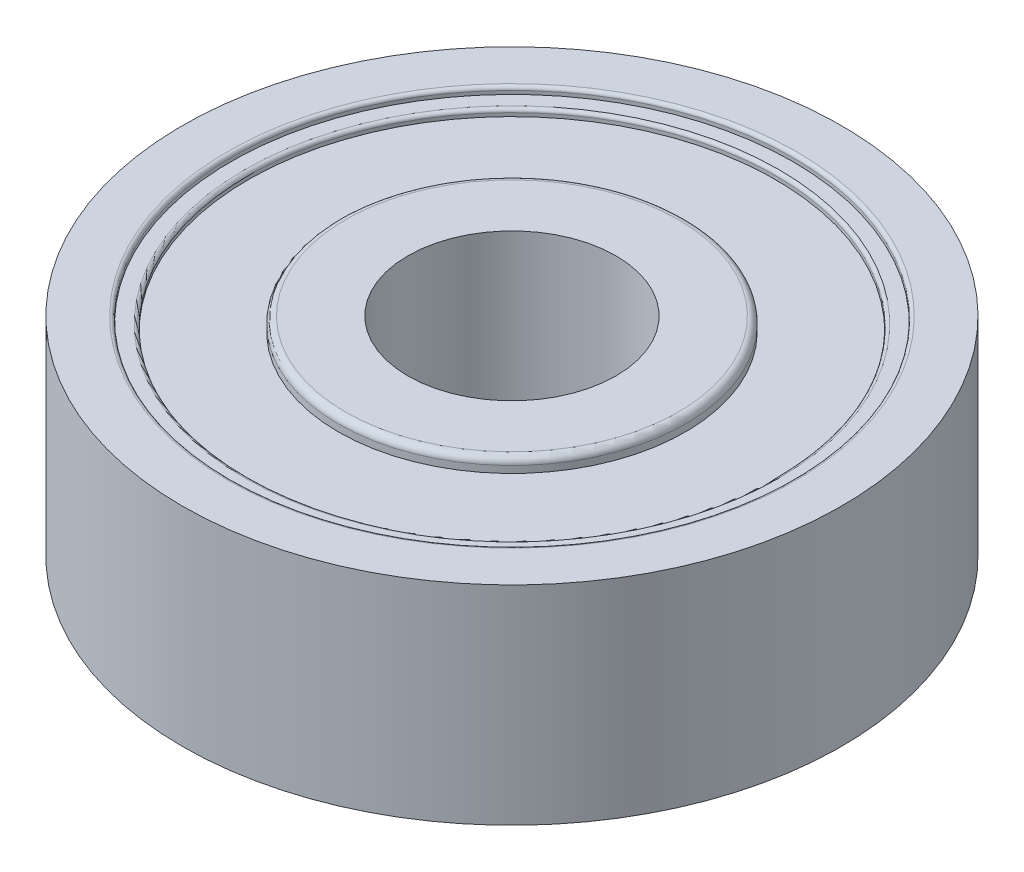
SolidWorks part; units mm, degrees
material "AISI 316 Barra de aço inoxidável recozido (SS)"
ref_plane "Plano frontal" through (0, 0, 0) normal (0, 0, 1) x (1, 0, 0)
ref_plane "Plano superior" through (0, 0, 0) normal (0, 1, 0) x (1, 0, 0)
ref_plane "Plano direito" through (0, 0, 0) normal (1, 0, 0) x (0, 0, -1)
sketch "Esboço1" plane through (0, 0, 0) normal (0, 1, 0) x (1, 0, 0)
  circle A0 centre (0, 0) radius 9.5
  dimension "D1" = 19
extrude "Ressalto-extrusão1" add sketch "Esboço1" along normal blind 6
sketch "Esboço2" plane through (0, 6, 0) normal (0, 1, 0) x (1, 0, 0)
  circle A0 centre (0, 0) radius 3
  dimension "D1" = 6
extrude "Corte-extrusão1" cut sketch "Esboço2" against normal blind 6
sketch "Esboço3" plane through (0, 6, 0) normal (0, 1, 0) x (1, 0, 0)
  circle A0 centre (0, 0) radius 8.1
  circle A1 centre (0, 0) radius 7.6
  dimension "D1" = 16.2
  dimension "D2" = 15.2
extrude "Corte-extrusão2" cut sketch "Esboço3" against normal blind 0.2
sketch "Esboço4" plane through (0, 6, 0) normal (0, 1, 0) x (1, 0, 0)
  circle A0 centre (0, 0) radius 5
  circle A1 centre (0, 0) radius 7.6 construction
  circle A2 centre (0, 0) radius 7.6
  dimension "D1" = 10
extrude "Corte-extrusão3" cut sketch "Esboço4" against normal blind 0.4
fillet "Filete1" radius 0.2 1 edges at (0, 6, 5)
fillet "Filete2" radius 0.1 2 edges at (0, 6, 8.1) (0, 5.8, 7.6)
ref_plane "Plano1" through (0, 3, 0) normal (0, 1, 0) x (1, 0, 0)
sketch "Esboço5" plane through (0, 0, 0) normal (0, 0, 1) x (1, 0, 0)
  line L1 (-9.5, 0) -> (10.1159, 0)
  line L2 (-9.5, 0) -> (-9.5, 3)
  line L3 (-9.5, 3) -> (10.1159, 3)
  line L4 (10.1159, 0) -> (10.1159, 3)
  dimension "D1" = 3
extrude "Corte-extrusão4" cut sketch "Esboço5" against normal mid plane 24
mirror "Espelhar7" about plane through (0, 3, 0) normal (0, 1, 0) of bodies 110
